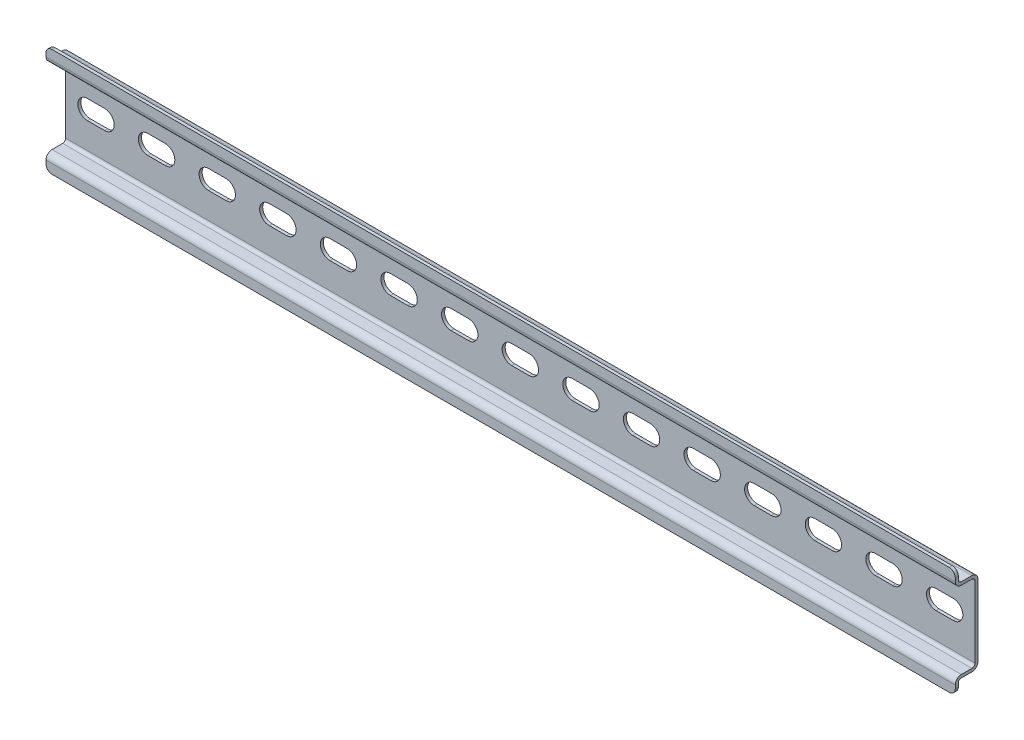
SolidWorks part; units mm, degrees
material "AISI 1045 Steel, cold drawn"
ref_plane "Front" through (0, 0, 0) normal (0, 0, 1) x (1, 0, 0)
ref_plane "Top" through (0, 0, 0) normal (0, 1, 0) x (1, 0, 0)
ref_plane "Right" through (0, 0, 0) normal (1, 0, 0) x (0, 0, -1)
sketch "Sketch1" plane through (0, 0, 0) normal (1, 0, 0) x (0, 0, -1)
  line L0 (0, 0) -> (0, 3.1)
  line L1 (2, 5.1) -> (5.5, 5.1)
  line L2 (6.5, 6.1) -> (6.5, 29.6)
  line L3 (5.5, 30.6) -> (2, 30.6)
  line L4 (0, 32.6) -> (0, 35.7)
  line L5 (6.5, 17.85) -> (-5.5369, 17.85) construction
  line L6 (1, 0) -> (1, 3.1)
  line L7 (2, 4.1) -> (5.5, 4.1)
  line L8 (7.5, 6.1) -> (7.5, 29.6)
  line L9 (5.5, 31.6) -> (2, 31.6)
  line L10 (1, 32.6) -> (1, 35.7)
  line L11 (0, 0) -> (1, 0)
  line L12 (0, 35.7) -> (1, 35.7)
  arc A0 (2, 30.6) -> (0, 32.6) centre (2, 32.6) cw
  arc A1 (0, 3.1) -> (2, 5.1) centre (2, 3.1) cw
  arc A2 (6.5, 29.6) -> (5.5, 30.6) centre (5.5, 29.6) ccw
  arc A3 (5.5, 5.1) -> (6.5, 6.1) centre (5.5, 6.1) ccw
  arc A4 (1, 3.1) -> (2, 4.1) centre (2, 3.1) cw
  arc A5 (5.5, 4.1) -> (7.5, 6.1) centre (5.5, 6.1) ccw
  arc A6 (7.5, 29.6) -> (5.5, 31.6) centre (5.5, 29.6) ccw
  arc A7 (2, 31.6) -> (1, 32.6) centre (2, 32.6) cw
  dimension "D1" = 2
  dimension "D2" = 1
  dimension "D3" = 6.5
  dimension "D4" = 35.7
  dimension "D5" = 25.5
  dimension "D6" = 1
extrude "Boss-Extrude1" add sketch "Sketch1" along normal blind 300
sketch "Sketch2" plane through (0, 0, 0) normal (0, 0, 1) x (1, 0, 0)
  line L0 (0, 17.85) -> (300, 17.85) construction
  line L1 (0, 29.6) -> (0, 6.1) construction
  line L2 (300, 29.6) -> (300, 6.1) construction
  line L3 (7.15, 17.85) -> (12.85, 17.85) construction
  line L4 (7.15, 21) -> (12.85, 21)
  line L5 (7.15, 14.7) -> (12.85, 14.7)
  arc A0 (7.15, 21) -> (7.15, 14.7) centre (7.15, 17.85) ccw
  arc A1 (12.85, 14.7) -> (12.85, 21) centre (12.85, 17.85) ccw
  point P8 (10, 17.85)
  dimension "D1" = 6.3
  dimension "D2" = 5.7
  dimension "D3" = 10
extrude "Cut-Extrude1" cut sketch "Sketch2" against normal through all
pattern_linear "LPattern1" count 15 spacing 20 along (1, 0, 0) of "Cut-Extrude1"
fillet "Fillet1" radius 2 4 edges at (300, 0, -0.5) (300, 35.7, -0.5) (0, 0, -0.5) (0, 35.7, -0.5)
equation "\"Length\"=300"
equation "\"D1@Boss-Extrude1\"=\"Length\""
equation "\"Hole Spacing\"= 20"
equation "\"D3@LPattern1\"=\"Hole Spacing\""
